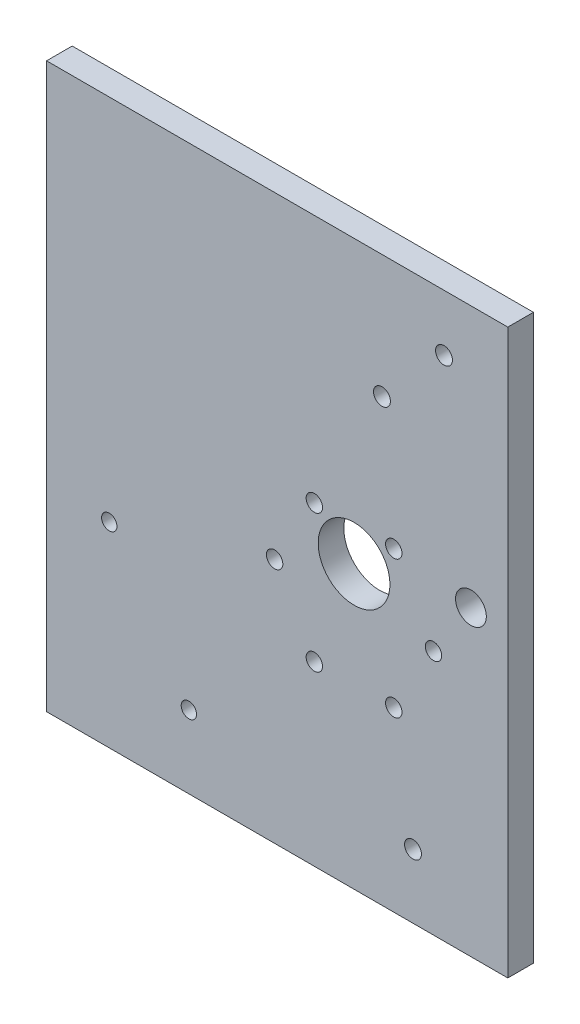
SolidWorks part; units mm, degrees
ref_plane "Front" through (0, 0, 0) normal (0, 0, 1) x (1, 0, 0)
ref_plane "Top" through (0, 0, 0) normal (0, 1, 0) x (1, 0, 0)
ref_plane "Right" through (0, 0, 0) normal (1, 0, 0) x (0, 0, -1)
sketch "Эскиз2" plane through (0, 0, 0) normal (0, 0, 1) x (1, 0, 0)
  line L0 (-25, 62) -> (-60, 62)
  line L5 (30, 62) -> (-25, 62)
  line L6 (30, 62) -> (30, -48)
  line L7 (30, -48) -> (-25, -48)
  line L9 (-60, 62) -> (-60, -48)
  line L10 (-60, -48) -> (-25, -48)
  circle A0 centre (0, 0) radius 15.5 construction
  circle A1 centre (-15.5, 0) radius 1.6
  circle A2 centre (-7.75, 13.4234) radius 1.6
  circle A3 centre (7.75, 13.4234) radius 1.6
  circle A4 centre (15.5, 0) radius 1.6
  circle A5 centre (7.75, -13.4234) radius 1.6
  circle A6 centre (-7.75, -13.4234) radius 1.6
  circle A8 centre (0, 7) radius 7
  dimension "D1" = 55
extrude "Бобышка-Вытянуть1" add sketch "Эскиз2" along normal blind 5
sketch "Эскиз4" plane through (0, 0, 5) normal (0, 0, 1) x (1, 0, 0)
  circle A0 centre (22.8079, 10.9896) radius 3.0043
extrude "Вырез-Вытянуть2" cut sketch "Эскиз4" against normal blind 10
sketch "Эскиз5" plane through (0, 0, 0) normal (0, 0, -1) x (-1, 0, 0)
  circle A0 centre (47.7653, -9.82) radius 1.5 construction
  circle A1 centre (32.2347, -33.82) radius 1.5 construction
  circle A2 centre (-11.5, -35.5) radius 1.65 construction
  circle A3 centre (-17.5517, 51) radius 1.65 construction
  circle A4 centre (-5.4483, 38) radius 1.65 construction
  circle A5 centre (47.7653, -9.82) radius 1.5
  circle A6 centre (32.2347, -33.82) radius 1.5
  circle A7 centre (-11.5, -35.5) radius 1.65
  circle A8 centre (-17.5517, 51) radius 1.65
  circle A9 centre (-5.4483, 38) radius 1.65
extrude "Вырез-Вытянуть3" cut sketch "Эскиз5" against normal blind 10 contours A8 | A9 | A6 | A5 | A7
